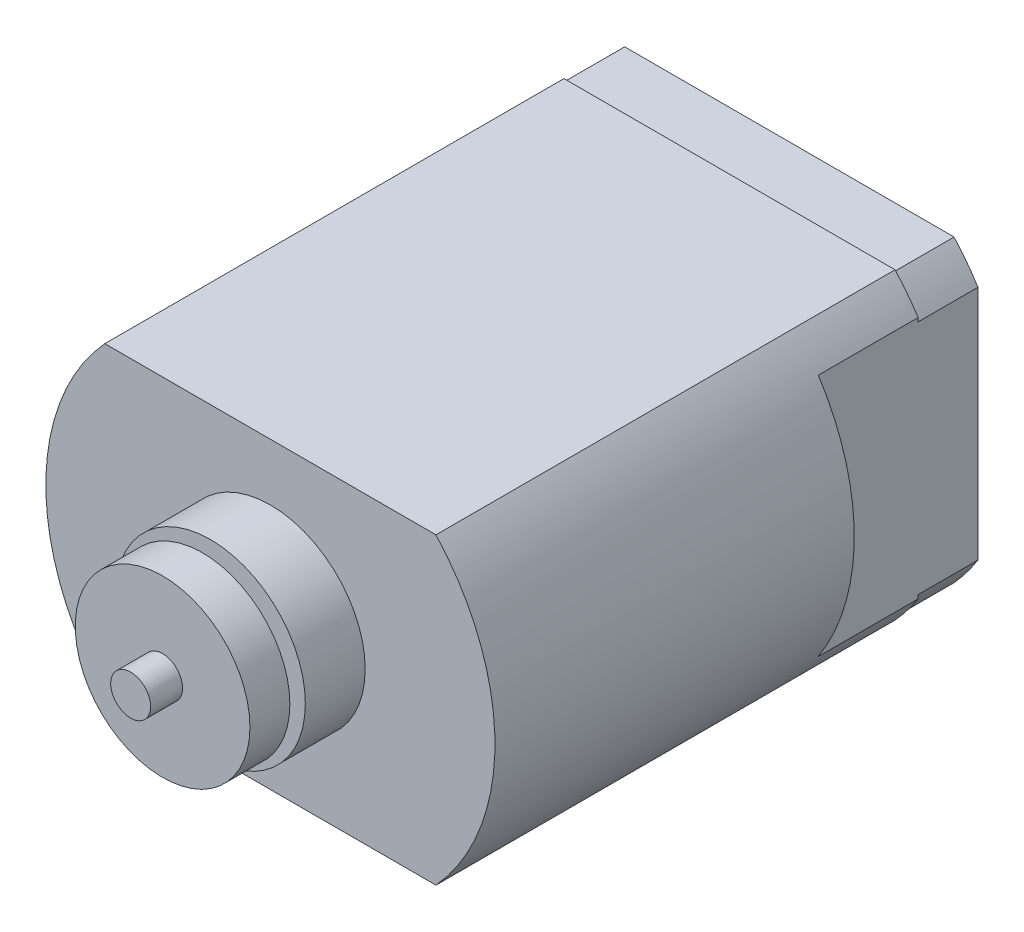
SolidWorks part; units mm, degrees
ref_plane "前视基准面" through (0, 0, 0) normal (0, 0, 1) x (1, 0, 0)
ref_plane "上视基准面" through (0, 0, 0) normal (0, 1, 0) x (1, 0, 0)
ref_plane "右视基准面" through (0, 0, 0) normal (1, 0, 0) x (0, 0, -1)
sketch "草图1" plane through (0, 0, 0) normal (0, 0, 1) x (1, 0, 0)
  line L0 (-11.25, 0) -> (11.25, 0) construction
  line L1 (-8.2947, 7.6) -> (8.2947, 7.6)
  line L2 (-8.2947, -7.6) -> (8.2947, -7.6)
  arc A0 (-8.2947, 7.6) -> (-8.2947, -7.6) centre (0, 0) ccw
  arc A1 (8.2947, -7.6) -> (8.2947, 7.6) centre (0, 0) ccw
  dimension "D1" = 22.5
  dimension "D2" = 15.2
extrude "凸台-拉伸1" add sketch "草图1" along normal blind 26
sketch "草图2" plane through (0, 0, 26) normal (0, 0, 1) x (1, 0, 0)
  circle A0 centre (0, 0) radius 4.75
  dimension "D1" = 9.5
extrude "凸台-拉伸2" add sketch "草图2" along normal blind 3
sketch "草图3" plane through (0, 0, 29) normal (0, 0, 1) x (1, 0, 0)
  circle A0 centre (0, 0) radius 1
  dimension "D1" = 2
extrude "凸台-拉伸3" add sketch "草图3" along normal blind 4
ref_plane "基准面1" through (0, 0, 31.4) normal (0, 0, 1) x (1, 0, 0)
sketch "草图4" plane through (0, 0, 31.4) normal (0, 0, 1) x (1, 0, 0)
  circle A0 centre (0, 0) radius 4.375
  dimension "D1" = 8.75
extrude "T20x0.4" add sketch "草图4" against normal blind 2
sketch "草图5" plane through (0, 0, 0) normal (0, 0, -1) x (-1, 0, 0)
  line L2 (8.2947, -7.6) -> (-8.2947, -7.6) construction
  line L3 (-8.2947, 7.6) -> (8.2947, 7.6) construction
  line L4 (8.2506, 7.5) -> (-8.2506, 7.5)
  line L5 (-8.2506, -7.5) -> (8.2506, -7.5)
  line L6 (8.2506, 7.5) -> (-8.2506, 7.5)
  line L7 (-8.2506, -7.5) -> (8.2506, -7.5)
  line L8 (8.2947, -7.6) -> (-8.2947, -7.6)
  line L9 (-8.2947, 7.6) -> (8.2947, 7.6)
  arc A2 (-8.2947, 7.6) -> (-8.2947, -7.6) centre (0, 0) ccw construction
  arc A3 (8.2947, -7.6) -> (8.2947, 7.6) centre (0, 0) ccw construction
  arc A4 (8.2506, -7.5) -> (8.2506, 7.5) centre (0, 0) ccw
  arc A5 (-8.2506, 7.5) -> (-8.2506, -7.5) centre (0, 0) ccw
  arc A6 (8.2506, -7.5) -> (8.2506, 7.5) centre (0, 0) ccw
  arc A7 (-8.2506, 7.5) -> (-8.2506, -7.5) centre (0, 0) ccw
  arc A8 (-8.2947, 7.6) -> (-8.2947, -7.6) centre (0, 0) ccw
  arc A9 (8.2947, -7.6) -> (8.2947, 7.6) centre (0, 0) ccw
  dimension "D1" = 0.1
extrude "切除-拉伸1" cut sketch "草图5" against normal blind 3
sketch "草图6" plane through (0, 0, 0) normal (0, 0, -1) x (-1, 0, 0)
  circle A0 centre (0, 0) radius 3.135
  dimension "D1" = 6.27
extrude "凸台-拉伸5" add sketch "草图6" along normal blind 2.5
sketch "草图7" plane through (0, 0, -2.5) normal (0, 0, -1) x (-1, 0, 0)
  circle A0 centre (0, 0) radius 1.25
  dimension "D1" = 2.5
extrude "切除-拉伸2" cut sketch "草图7" against normal blind 1
sketch "草图8" plane through (0, 0, 0) normal (0, 0, -1) x (-1, 0, 0)
  line L0 (8.2947, 7.6) -> (-8.2947, 7.6) construction
  line L1 (-9.45, 7.6) -> (-11.25, 7.6)
  line L2 (-9.45, 7.6) -> (-9.45, -7.6)
  line L3 (-9.45, -7.6) -> (-11.25, -7.6)
  line L4 (-11.25, 7.6) -> (-11.25, -7.6)
  line L5 (-9.45, 7.6) -> (-11.25, -7.6) construction
  line L6 (-9.45, -7.6) -> (-11.25, 7.6) construction
  line L7 (-8.2947, -7.6) -> (8.2947, -7.6) construction
  line L8 (11.25, 0) -> (11.25, 7.6) construction
  arc A0 (-8.2947, 7.6) -> (-8.2947, -7.6) centre (0, 0) ccw construction
  arc A1 (8.2947, -7.6) -> (8.2947, 7.6) centre (0, 0) ccw construction
  point P4 (-10.35, 0)
  dimension "D1" = 20.7
extrude "切除-拉伸3" cut sketch "草图8" against normal blind 8
